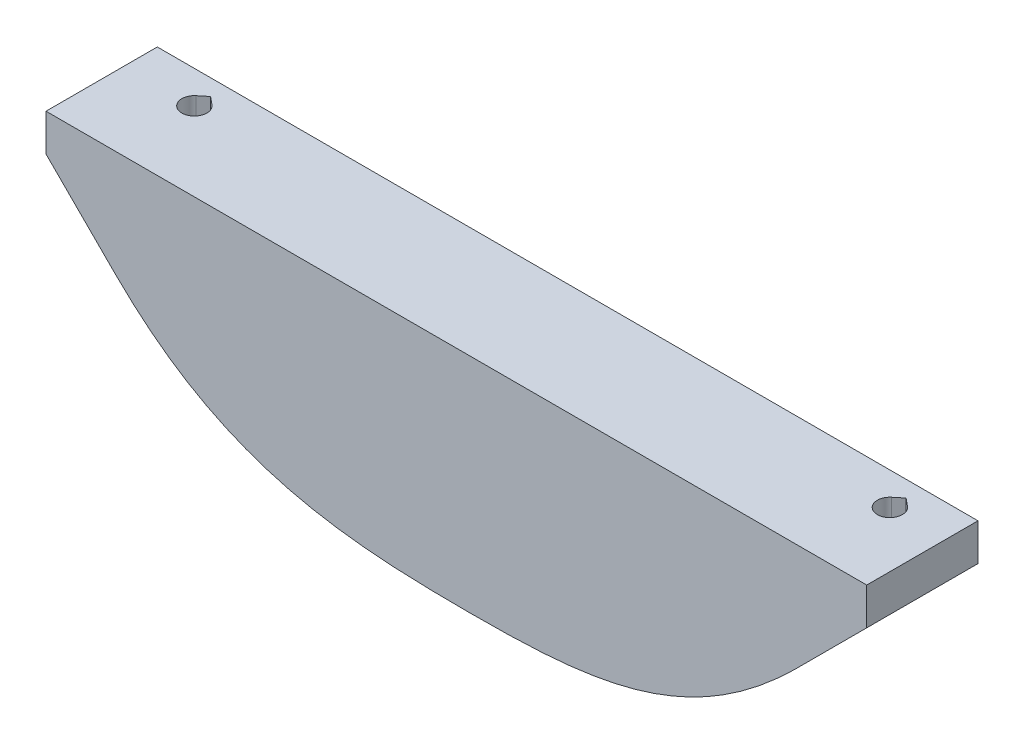
SolidWorks part; units mm, degrees
ref_plane "Front Plane" through (0, 0, 0) normal (0, 0, 1) x (1, 0, 0)
ref_plane "Top Plane" through (0, 0, 0) normal (0, 1, 0) x (1, 0, 0)
ref_plane "Right Plane" through (0, 0, 0) normal (1, 0, 0) x (0, 0, -1)
sketch "Sketch1" plane through (0, 0, 0) normal (0, 0, 1) x (1, 0, 0)
  line L0 (88.5, -40) -> (76.5, -40) construction
  line L1 (15, -40) -> (0, -40) construction
  line L2 (88.5, -40) -> (76.5, -40)
  line L3 (15, -40) -> (0, -40)
  line L4 (15, -40) -> (76.5, -40) construction
  line L5 (45.75, -40) -> (45.75, -54) construction
  line L6 (15, -40) -> (15, -44)
  line L7 (0, -40) -> (0, -44)
  line L8 (63.1923, -54) -> (28.3077, -54) construction
  line L9 (15, -59.2382) -> (15, -24.9064) construction
  line L10 (0, -44) -> (7.5, -51.5)
  line L11 (45.75, -54) -> (45.75, -64) construction
  line L12 (62.5753, -64) -> (28.9247, -64) construction
  line L13 (15.3084, -59.3084) -> (-3.2087, -40.7913) construction
  line L14 (88.5, -40) -> (88.5, -44)
  line L15 (76.5, -40) -> (76.5, -44)
  line L16 (30.6262, -54) -> (60.8738, -54) construction
  line L17 (76.5, -54.9076) -> (76.5, -28.2556) construction
  line L18 (88.5, -44) -> (81, -51.5)
  line L19 (29.8261, -64) -> (61.6739, -64) construction
  line L20 (72.761, -59.739) -> (90.8899, -41.6101) construction
  spline S0 degree 3 poles (15, -44) (15, -49.9374) (29.668, -54) (45.75, -54) knots 0 0 0 0 1 1 1 1
  spline S1 degree 3 poles (7.5, -51.5) (19.0732, -63.0732) (31.7289, -64) (45.75, -64) knots 0 0 0 0 1 1 1 1
  spline S2 degree 3 poles (76.5, -44) (76.5, -50.4452) (58.3532, -54) (45.75, -54) knots 0 0 0 0 1 1 1 1
  spline S3 degree 3 poles (81, -51.5) (69.4421, -63.0579) (59.0199, -64) (45.75, -64) knots 0 0 0 0 1 1 1 1
  dimension "D1" = 14
  dimension "D2" = 4
  dimension "D3" = 7.5
  dimension "D4" = 45
  dimension "D5" = 10
  dimension "D6" = 7.5
  dimension "D7" = 45
extrude "Boss-Extrude1" add sketch "Sketch1" against normal blind 12
sketch "Sketch2" plane through (0, -40, 0) normal (0, 1, 0) x (1, 0, 0)
  line L0 (0, 12) -> (15, 0) construction
  line L1 (76.5, 12) -> (88.5, 0) construction
  line L2 (82.5, 6) -> (82.5, 8.5) construction
  line L5 (7.5, 6) -> (7.5, 8.5) construction
  line L6 (7.5, 12) -> (7.5, 0) construction
  circle A0 centre (7.5, 6) radius 1.35 construction
  circle A1 centre (82.5, 6) radius 1.35 construction
  circle A2 centre (82.5, 8.5) radius 1.35
  circle A3 centre (7.5, 8.5) radius 1.35
  dimension "D1" = 2.7
  dimension "D2" = 2.5
extrude "Cut-Extrude1" cut sketch "Sketch2" against normal through all
ref_plane "Plane1" through (0, -80, 0) normal (0, 1, 0) x (1, 0, 0)
sketch "Sketch4" plane through (0, -80, 0) normal (0, 1, 0) x (1, 0, 0)
  circle A0 centre (7.5, 8.5) radius 2.5
  circle A1 centre (82.5, 8.5) radius 2.5
  circle A2 centre (82.5, 8.5) radius 1.35 construction
  dimension "D1" = 5
extrude "Cut-Extrude3" cut sketch "Sketch4" along normal offset from surface (37 mm away) 3 up to face at (7.5, -40, -7.15)
sketch "Sketch7" plane through (0, -40, 0) normal (0, 1, 0) x (1, 0, 0)
  line L2 (7.5, 9.85) -> (7.5, 10.25) construction
  line L5 (7.5, 10.25) -> (8.359, 9.5414)
  line L6 (7.5, 10.25) -> (6.641, 9.5414)
  arc A2 (8.359, 9.5414) -> (6.641, 9.5414) centre (7.5, 8.5) ccw
  circle A13 centre (7.5, 8.5) radius 1.35 construction
  dimension "D1" = 0.4
extrude "Cut-Extrude4" cut sketch "Sketch7" against normal through all
sketch "Sketch8" plane through (0, -40, 0) normal (0, 1, 0) x (1, 0, 0)
  line L0 (82.5, 9.85) -> (82.5, 10.25) construction
  line L1 (82.5, 10.25) -> (83.359, 9.5414)
  line L2 (82.5, 10.25) -> (81.641, 9.5414)
  circle A0 centre (82.5, 8.5) radius 1.35 construction
  arc A1 (83.359, 9.5414) -> (81.641, 9.5414) centre (82.5, 8.5) ccw
  dimension "D1" = 0.4
extrude "Cut-Extrude5" cut sketch "Sketch8" against normal through all
sketch "Sketch9" plane through (0, 0, 0) normal (0, 0, 1) x (1, 0, 0)
  line L0 (76.5, -40) -> (76.5, -44) construction
  line L1 (15, -44) -> (15, -40) construction
  line L2 (76.5, -40) -> (76.5, -44)
  line L3 (15, -44) -> (15, -40)
  line L4 (15, -40) -> (76.5, -40)
  spline S0 degree 3 poles (-1916.2196, 114.5228) (2277.9042, -54.4367) (-2168.6779, -190.2087) (2029.7998, 191.9728) knots -3.734209 -3.734209 -3.734209 -3.734209 5.268471 5.268471 5.268471 5.268471 only from (76.5, -44) to (45.75, -54) construction
  spline S1 degree 3 poles (-1804.2139, 690.1886) (2293.6186, -535.9232) (-2233.596, 176.6404) (2013.315, -43.9881) knots -5.534508 -5.534508 -5.534508 -5.534508 5.414963 5.414963 5.414963 5.414963 only from (45.75, -54) to (15, -44) construction
  spline S2 degree 3 poles (76.5, -44) (76.5, -50.4452) (58.3532, -54) (45.75, -54) knots 0 0 0 0 1 1 1 1
  spline S3 degree 3 poles (45.75, -54) (29.668, -54) (15, -49.9374) (15, -44) knots 0 0 0 0 1 1 1 1
extrude "Boss-Extrude2" add sketch "Sketch9" against normal up to surface (12 mm away) up to face at (44.5, -46.4167, -12)
